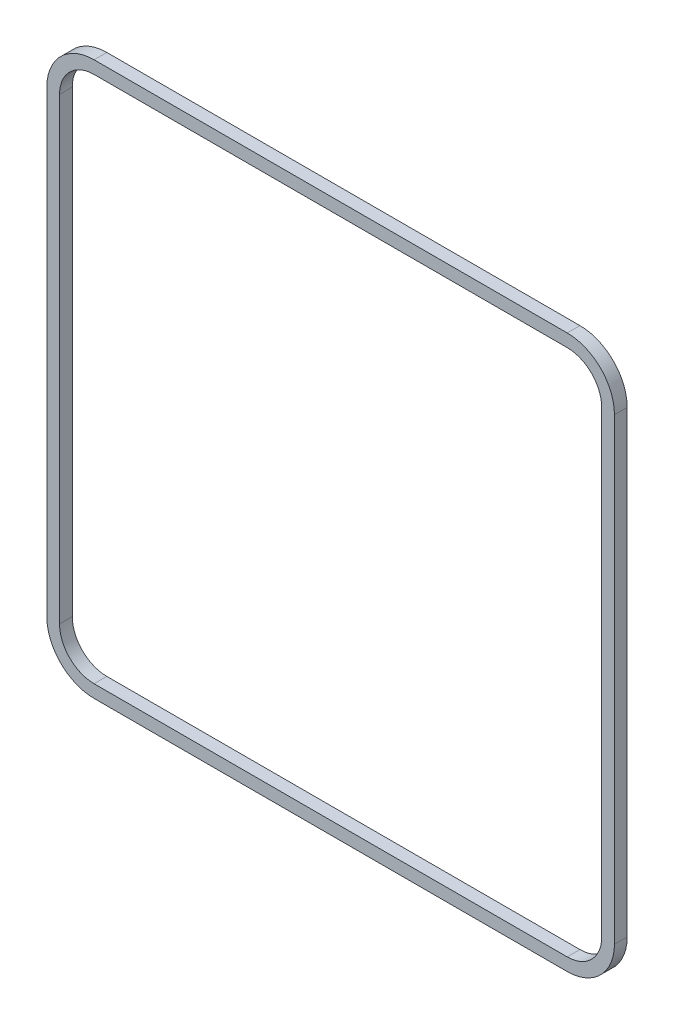
SolidWorks part; units mm, degrees
ref_plane "Front Plane" through (0, 0, 0) normal (0, 0, 1) x (1, 0, 0)
ref_plane "Top Plane" through (0, 0, 0) normal (0, 1, 0) x (1, 0, 0)
ref_plane "Right Plane" through (0, 0, 0) normal (1, 0, 0) x (0, 0, -1)
sketch "Sketch1" plane through (0, 0, 0) normal (0, 0, 1) x (1, 0, 0)
  line L0 (4.7625, -1.905) -> (70.8787, -1.905) construction
  line L1 (4.7625, 0) -> (70.8787, 0) construction
  line L2 (0, 4.7625) -> (0, 68.8467) construction
  line L3 (4.7625, 73.6092) -> (70.8787, 73.6092) construction
  line L4 (75.6412, 4.7625) -> (75.6412, 68.8467) construction
  line L5 (77.5462, 4.7625) -> (77.5462, 68.8467) construction
  line L6 (4.7625, 75.5142) -> (70.8787, 75.5142) construction
  line L7 (-1.905, 4.7625) -> (-1.905, 68.8467) construction
  line L8 (-0.0635, 4.7625) -> (-0.0635, 68.8467)
  line L9 (4.7625, 73.6727) -> (70.8787, 73.6727)
  line L10 (75.7047, 4.7625) -> (75.7047, 68.8467)
  line L11 (4.7625, -0.0635) -> (70.8787, -0.0635)
  line L12 (-1.8415, 4.7625) -> (-1.8415, 68.8467)
  line L13 (4.7625, 75.4507) -> (70.8787, 75.4507)
  line L14 (77.4827, 4.7625) -> (77.4827, 68.8467)
  line L15 (4.7625, -1.8415) -> (70.8787, -1.8415)
  arc A0 (4.7625, 0) -> (0, 4.7625) centre (4.7625, 4.7625) cw construction
  arc A1 (70.8787, 0) -> (75.6412, 4.7625) centre (70.8787, 4.7625) ccw construction
  arc A2 (75.6412, 68.8467) -> (70.8787, 73.6092) centre (70.8787, 68.8467) ccw construction
  arc A3 (4.7625, 73.6092) -> (0, 68.8467) centre (4.7625, 68.8467) ccw construction
  arc A4 (70.8787, -1.905) -> (77.5462, 4.7625) centre (70.8787, 4.7625) ccw construction
  arc A5 (77.5462, 68.8467) -> (70.8787, 75.5142) centre (70.8787, 68.8467) ccw construction
  arc A6 (4.7625, 75.5142) -> (-1.905, 68.8467) centre (4.7625, 68.8467) ccw construction
  arc A7 (4.7625, -1.905) -> (-1.905, 4.7625) centre (4.7625, 4.7625) cw construction
  arc A8 (4.7625, 73.6727) -> (-0.0635, 68.8467) centre (4.7625, 68.8467) ccw
  arc A9 (75.7047, 68.8467) -> (70.8787, 73.6727) centre (70.8787, 68.8467) ccw
  arc A10 (70.8787, -0.0635) -> (75.7047, 4.7625) centre (70.8787, 4.7625) ccw
  arc A11 (4.7625, -0.0635) -> (-0.0635, 4.7625) centre (4.7625, 4.7625) cw
  arc A12 (4.7625, 75.4507) -> (-1.8415, 68.8467) centre (4.7625, 68.8467) ccw
  arc A13 (77.4827, 68.8467) -> (70.8787, 75.4507) centre (70.8787, 68.8467) ccw
  arc A14 (70.8787, -1.8415) -> (77.4827, 4.7625) centre (70.8787, 4.7625) ccw
  arc A15 (4.7625, -1.8415) -> (-1.8415, 4.7625) centre (4.7625, 4.7625) cw
  point P7 (0, 0)
  point P10 (75.6412, 0)
  point P13 (75.6412, 73.6092)
  point P16 (0, 73.6092)
  dimension "D3" = 4.7625
  dimension "D1" = 75.6412
  dimension "D2" = 73.6092
  dimension "D4" = 1.905
  dimension "D5" = 0.0635
  dimension "D6" = 1.778
extrude "Boss-Extrude1" add sketch "Sketch1" along normal blind 1.778
